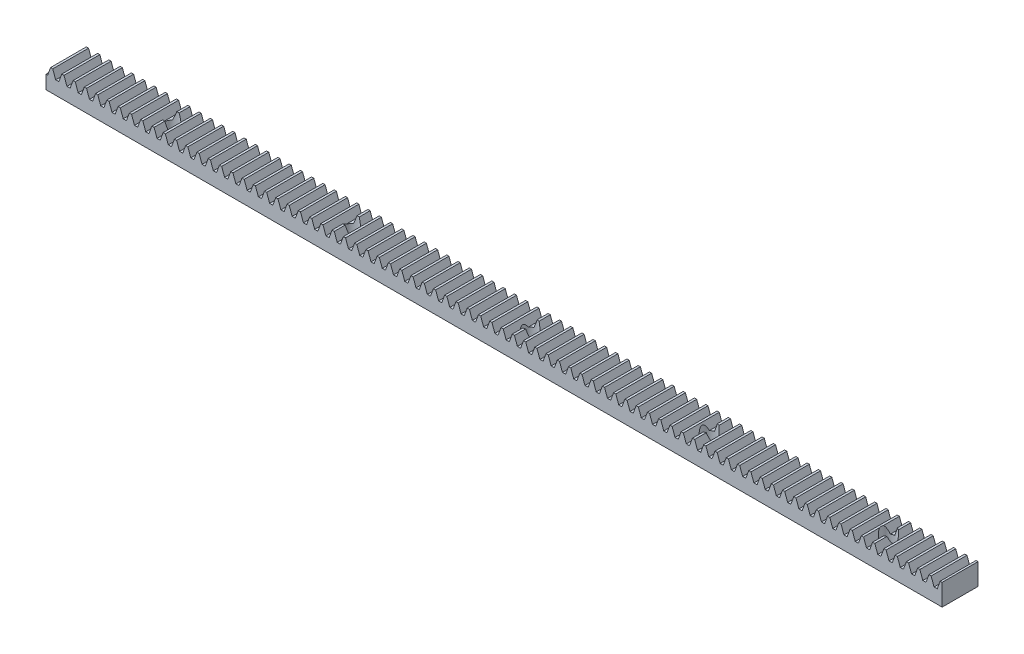
SolidWorks part; units mm, degrees
extrude "Blank" add sketch "BlankSke" against normal blind 10
sketch "BlankSke" plane through (0, 0, 0) normal (0, 0, 1) x (1, 0, 0)
  line L1 (0, 0) -> (300, 0)
  line L2 (0, 0) -> (0, 6)
  line L3 (0, 6) -> (300, 6)
  line L4 (300, 0) -> (300, 6)
  dimension "Length" = 300
  dimension "Blank_height" = 6
ref_plane "Plane1" through (0, 0, 0) normal (0, 0, 1) x (1, 0, 0)
ref_plane "Plane2" through (0, 0, 0) normal (0, 1, 0) x (1, 0, 0)
ref_plane "Plane3" through (0, 0, 0) normal (1, 0, 0) x (0, 0, -1)
sketch "HoldingSke" plane through (0, 0, 0) normal (0, 1, 0) x (1, 0, 0)
  line L0 (0, 0) -> (0.1392, 0.9903)
  line L1 (-15, 0) -> (100, 0) construction
  line L2 (0, 0) -> (-2.1039, 2.3779)
  line L3 (0, 0) -> (-11.863, 4.5341)
  line L4 (0, 0) -> (-1.0524, 8.5716)
  line L5 (0, 0) -> (-23.7986, -8.8762)
  line L6 (0, 0) -> (-10.5278, -7.1032)
  line L9 (-71.009, 38.7566) -> (210.8988, 141.3627)
  line L10 (-76.2, 3.3779) -> (-71.2, 3.3779)
  line L11 (0, 0) -> (-10, 0)
  line L12 (-76.2, 101.6) -> (-76.162, 101.6)
  line L13 (24.9733, 27.94) -> (52.9518, 28.4284)
  line L14 (24.9733, 27.94) -> (24.9743, 27.94)
  line L15 (24.9733, 27.94) -> (100.4006, 29.5858)
  circle A0 centre (0, 0) radius 19.05
  circle A1 centre (0, 0) radius 2.5
  circle A2 centre (0, 0) radius 12.7
  dimension "MPH" = 5
  dimension "Diameter" = 38.1
  dimension "Num_teeth" = 97
  dimension "Pitch" = 1
  dimension "Show_teeth" = 998
  dimension "Thickness" = 12.7
  dimension "Ap" = 20
  dimension "Pitch_height" = 5
  dimension "Width" = 10
  dimension "Backlash" = 0.038
  dimension "Addendum_fac" = 1
  dimension "Dedendum_fac" = 1.25
  dimension "Clearance_fac" = 0.25
  dimension "Dedendum_add" = 0.001
  dimension "Length" = 300
  dimension "Module" = 1
sketch "TooCutSkeIll" plane through (0, 0, 0) normal (0, 0, 1) x (1, 0, 0)
  line L0 (-1.2538, 5.9737) -> (-0.5045, 3.9152)
  line L1 (-0.2687, 3.75) -> (0.2687, 3.75)
  line L2 (0.5045, 3.9152) -> (1.2538, 5.9737)
  line L3 (300, 6) -> (0, 6) construction
  line L4 (0, 0) -> (0, 64.897) construction
  line L5 (-13.208, 5) -> (12.954, 5) construction
  line L6 (0, 0) -> (300, 0) construction
  line L7 (0.8994, 5) -> (0.8994, 48.7463) construction
  line L8 (-0.8994, 5) -> (-0.8994, 48.7463) construction
  line L9 (1.2914, 6) -> (1.2914, 6.0254)
  line L10 (-1.2914, 6) -> (-1.2914, 6.0254)
  line L11 (-1.2914, 6.0254) -> (1.2914, 6.0254)
  arc A0 (0.2687, 3.75) -> (0.5045, 3.9152) centre (0.2687, 4.001) ccw
  arc A1 (-0.5045, 3.9152) -> (-0.2687, 3.75) centre (-0.2687, 4.001) ccw
  arc A2 (1.2914, 6) -> (1.2538, 5.9737) centre (1.2914, 5.96) ccw
  arc A3 (-1.2538, 5.9737) -> (-1.2914, 6) centre (-1.2914, 5.96) ccw
  dimension "Pitch_height" = 5
  dimension "Addendum_plus" = 1.0254
  dimension "Pressure_angle" = 20
  dimension "Gap_width" = 1.7988
  dimension "Dedendum" = 1.25
extrude "ToothCutIll" [suppressed] cut sketch "TooCutSkeIll" against normal through all
sketch "TooCutSkeSim" plane through (0, 0, 0) normal (0, 0, 1) x (1, 0, 0)
  line L0 (0.4444, 3.75) -> (-0.4444, 3.75)
  line L1 (1.2726, 6.0254) -> (0.4444, 3.75)
  line L2 (0, 17.4625) -> (0, 53.467) construction
  line L3 (1.2726, 6.0254) -> (-1.2726, 6.0254)
  line L6 (-1.2726, 6.0254) -> (-0.4444, 3.75)
  line L9 (-0.8994, 5) -> (0.8994, 5) construction
  line L10 (0, 0) -> (300, 0) construction
  line L11 (0.8994, 5) -> (0.8994, 53.467) construction
  line L12 (-0.8994, 5) -> (-0.8994, 53.467) construction
  dimension "Pitch_height" = 5
  dimension "Addendum_plus" = 1.0254
  dimension "Pressure_angle" = 20
  dimension "Gap_width" = 1.7988
  dimension "Dedendum" = 1.25
extrude "ToothCutSim" cut sketch "TooCutSkeSim" against normal through all
pattern_linear "TeethCuts" count 96 spacing 3.1416 along (1, 0, 0) of "ToothCutIll", "ToothCutSim"
sketch "草图1" plane through (0, 0, 0) normal (0, 1, 0) x (1, 0, 0)
  line L0 (0, 0) -> (300, 0) construction
  line L1 (0, 10) -> (0, 0) construction
  circle A0 centre (30, 5) radius 2
  circle A1 centre (80, 5) radius 2
  circle A2 centre (130, 5) radius 2
  circle A3 centre (180, 5) radius 2
  circle A4 centre (230, 5) radius 2
  dimension "D3" = 4
  dimension "D1" = 5
  dimension "D2" = 30
  dimension "D5" = 50
  dimension "D4" = 5
extrude "切除-拉伸1" cut sketch "草图1" along normal through all
sketch "草图2" plane through (0, 0, 0) normal (0, 1, 0) x (1, 0, 0)
  line L1 (300, 10) -> (250, 10)
  line L2 (300, 10) -> (300, 0)
  line L3 (300, 0) -> (250, 0)
  line L4 (250, 10) -> (250, 0)
  dimension "D1" = 50
extrude "切除-拉伸2" cut sketch "草图2" along normal blind 10
equation "' \"Module@HoldingSke\" = 6.35"
equation "' \"Num_teeth@HoldingSke\" = 12"
equation "' \"Ap@HoldingSke\" =  20"
equation "' \"Ap@HoldingSke\" = 20"
equation "' \"Width@HoldingSke\" = 0.25 * 25.4"
equation "' \"Show_teeth@HoldingSke\" = 500"
equation "' \"Backlash@HoldingSke\" = 0.009 * 25.4"
equation "' \"Addendum_fac@HoldingSke\" = 1.0"
equation "' \"Dedendum_fac@HoldingSke\" = 1.25"
equation "' \"Dedendum_add@HoldingSke\" = 0.00005 * 25.4"
equation "' \"Clearance_fac@HoldingSke\" = 0.25"
equation "' \"Pitch_height@HoldingSke\" = 1 * 25.4"
equation "' \"Length@HoldingSke\" = 4.71 * 25.4"
equation "\"Pitch@HoldingSke\" = 1 / \"Module@HoldingSke\""
equation "\"MPH@HoldingSke\" = \"Dedendum_fac@HoldingSke\" / \"Pitch@HoldingSke\" + 2 * \"Dedendum_add@HoldingSke\" + 0.002 * 25.4"
equation "\"MPH@HoldingSke\" = ((sgn( \"MPH@HoldingSke\" - \"Pitch_height@HoldingSke\")+1)*( \"MPH@HoldingSke\" - \"Pitch_height@HoldingSke\"))/2 + \"Pitch_height@HoldingSke\""
equation "\"Blank_height@BlankSke\" = \"Pitch_height@HoldingSke\" + \"Addendum_fac@HoldingSke\"  / \"Pitch@HoldingSke\" "
equation "\"Length@BlankSke\" =  \"Length@HoldingSke\""
equation "\"Face_width@Blank\" = \"Width@HoldingSke\""
equation "\"Pressure_angle@TooCutSkeIll\" = \"Ap@HoldingSke\""
equation "\"Addendum_plus@TooCutSkeIll\" =  \"Addendum_fac@HoldingSke\"  / \"Pitch@HoldingSke\" + 0.001 *25.4"
equation "\"Dedendum@TooCutSkeIll\" = \"Dedendum_fac@HoldingSke\"  / \"Pitch@HoldingSke\""
equation "\"Pitch_height@TooCutSkeIll\" =  \"MPH@HoldingSke\""
equation "\"Gap_width@TooCutSkeIll\" = 3.14159265 / 2 / \"Pitch@HoldingSke\" + 6 * \"Backlash@HoldingSke\""
equation "\"Pressure_angle@TooCutSkeSim\" = \"Ap@HoldingSke\""
equation "\"Addendum_plus@TooCutSkeSim\" =  \"Addendum_fac@HoldingSke\"  / \"Pitch@HoldingSke\" + 0.001 * 25.4"
equation "\"Dedendum@TooCutSkeSim\" = \"Dedendum_fac@HoldingSke\"  / \"Pitch@HoldingSke\""
equation "\"Pitch_height@TooCutSkeSim\" =  \"MPH@HoldingSke\""
equation "\"Gap_width@TooCutSkeSim\" = 3.14159265 / 2 / \"Pitch@HoldingSke\" + 6 * \"Backlash@HoldingSke\""
equation "\"Root_fillet@TooCutSkeIll\" = \"Clearance_fac@HoldingSke\" / \"Pitch@HoldingSke\" + \"Dedendum_add@HoldingSke\""
equation "\"Break_rad@TooCutSkeIll\" = 0.02 / \"Pitch@HoldingSke\" * 2"
equation "\"Linear_pitch@TeethCuts\" = 3.14159265 / \"Pitch@HoldingSke\""
equation "\"Num_teeth@HoldingSke\" = int( ( \"Length@HoldingSke\" + 0 ) / (3.14159265 / \"Pitch@HoldingSke\")) + 0.9999  + 1"
equation " \"Num_teeth@TeethCuts\" = int( \"Show_teeth@HoldingSke\" ) + 1"
equation " \"Num_teeth@TeethCuts\" = ((sgn( \"Num_teeth@TeethCuts\" - \"Num_teeth@HoldingSke\" )-1)*( \"Num_teeth@TeethCuts\" - \"Num_teeth@HoldingSke\" ))/-2+ \"Num_teeth@HoldingSke\""
equation " \"Num_teeth@TeethCuts\" = ((sgn( \"Num_teeth@TeethCuts\" - 2.0)+1)*( \"Num_teeth@TeethCuts\" - 2.0))/2 +2.0"
